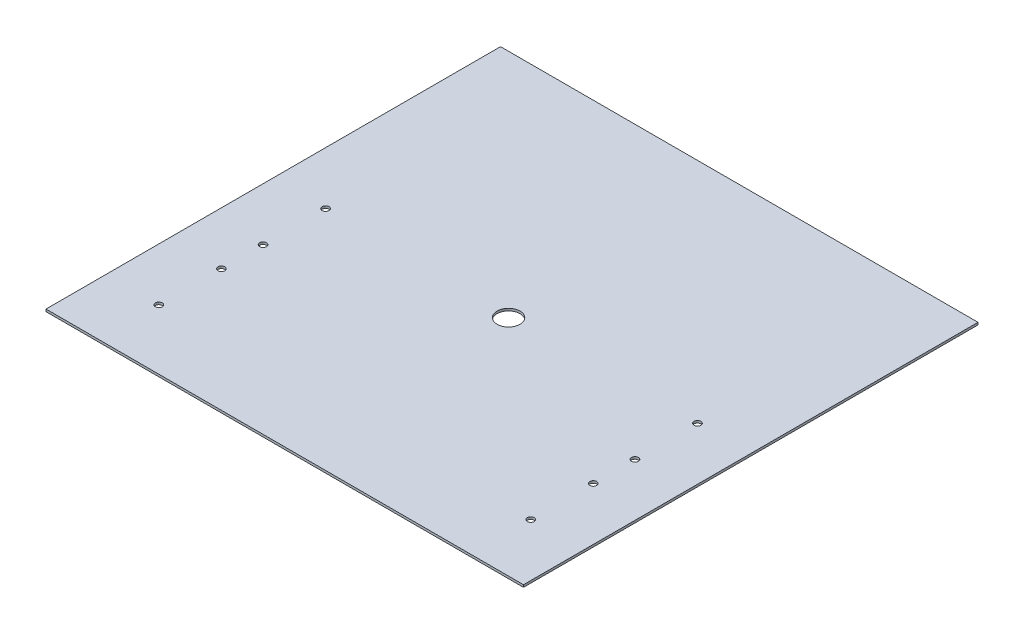
SolidWorks part; units mm, degrees
ref_plane "Front Plane" through (0, 0, 0) normal (0, 0, 1) x (1, 0, 0)
ref_plane "Top Plane" through (0, 0, 0) normal (0, 1, 0) x (1, 0, 0)
ref_plane "Right Plane" through (0, 0, 0) normal (1, 0, 0) x (0, 0, -1)
sketch "Sketch1" plane through (0, 0, 0) normal (0, 1, 0) x (1, 0, 0)
  line L1 (0, 0) -> (208, 0)
  line L2 (0, 0) -> (0, 198)
  line L3 (0, 198) -> (208, 198)
  line L4 (208, 0) -> (208, 198)
  dimension "D1" = 208
  dimension "D2" = 198
extrude "Boss-Extrude1" add sketch "Sketch1" along normal blind 1
sketch "Input for speaker" plane through (0, 1, 0) normal (0, 1, 0) x (1, 0, 0)
  line L0 (208, 0) -> (208, 198) construction
  line L1 (208, 198) -> (0, 198) construction
  line L7 (104, 198) -> (104, 0) construction
  line L8 (104, 97.5) -> (0, 97.5) construction
  line L9 (104, 97.5) -> (208, 97.5) construction
  line L10 (0, 0) -> (208, 0) construction
  line L11 (0, 198) -> (0, 0) construction
  circle A0 centre (104, 97.5) radius 5
  point P0 (104, 0)
  point P12 (203, 82.5749)
  point P13 (5, 82.6493)
  point P14 (104, 97.5)
  point P19 (0, 97.5)
  dimension "D3" = 10
  dimension "D4" = 97.5
extrude "Cut-Extrude1" cut sketch "Input for speaker" against normal blind 10 contours A0
sketch "Sketch4" plane through (0, 0, 0) normal (0, -1, 0) x (-1, 0, 0)
  line L0 (-104, 198) -> (-104, 0) construction
  line L1 (-208, 198) -> (0, 198) construction
  line L2 (0, 0) -> (-208, 0) construction
  circle A0 centre (-185, 98.7978) radius 1.5
  circle A2 centre (-185, 71.5578) radius 1.5
  circle A3 centre (-185, 53.4) radius 1.5
  circle A4 centre (-185, 26.16) radius 1.5
  circle A5 centre (-23, 26.16) radius 1.5
  circle A6 centre (-23, 53.4) radius 1.5
  circle A7 centre (-23, 71.5578) radius 1.5
  circle A8 centre (-23, 98.7978) radius 1.5
  dimension "D1" = 3
  dimension "D2" = 3
  dimension "D3" = 3
  dimension "D4" = 3
extrude "Cut-Extrude2" cut sketch "Sketch4" against normal blind 1
